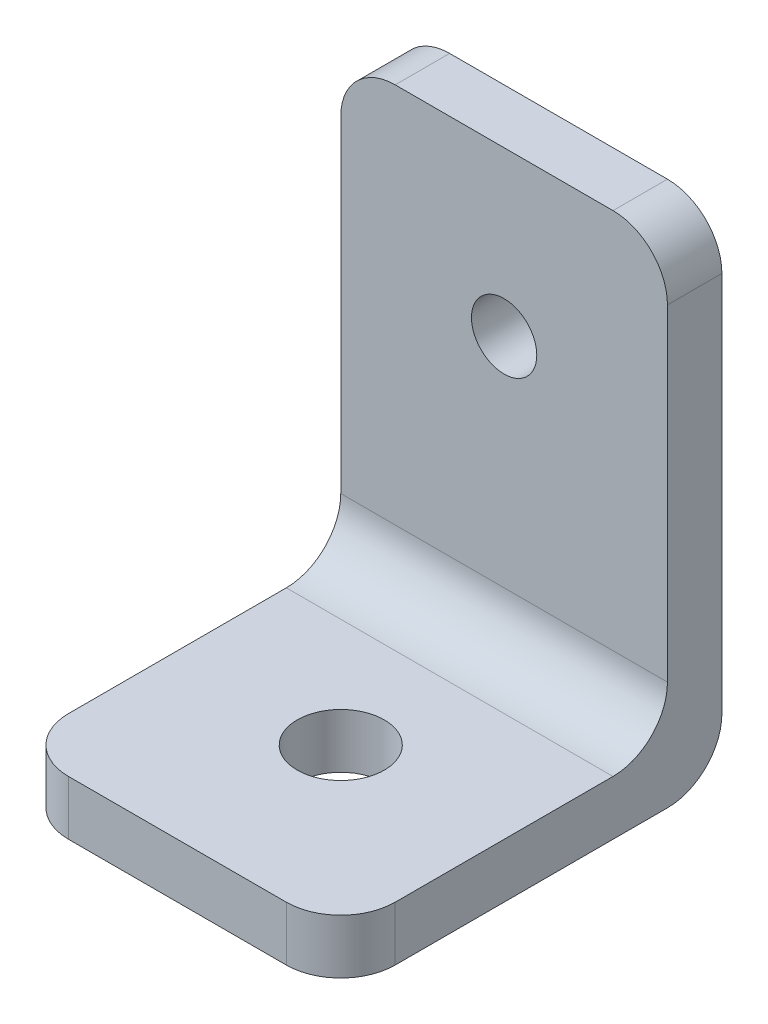
SolidWorks part; units mm, degrees
material "1023 Carbon Steel Sheet (SS)"
ref_plane "Front Plane" through (0, 0, 0) normal (0, 0, 1) x (1, 0, 0)
ref_plane "Top Plane" through (0, 0, 0) normal (0, 1, 0) x (1, 0, 0)
ref_plane "Right Plane" through (0, 0, 0) normal (1, 0, 0) x (0, 0, -1)
sketch "Sketch1" plane through (0, 0, 0) normal (0, 0, 1) x (1, 0, 0)
  line L0 (0, 0) -> (0, 45)
  line L1 (0, 45) -> (30, 45)
  line L2 (30, 45) -> (30, 0)
  line L3 (30, 0) -> (0, 0)
  line L4 (15, 45) -> (15, 30) construction
  circle A0 centre (15, 30) radius 3
extrude "Boss-Extrude1" add sketch "Sketch1" along normal blind 5
sketch "Sketch2" plane through (0, 0, 5) normal (0, 0, 1) x (1, 0, 0)
  line L0 (30, 0) -> (30, 45) construction
  line L1 (0, 0) -> (30, 0)
  line L2 (0, 0) -> (0, 5)
  line L3 (0, 5) -> (30, 5)
  line L4 (30, 0) -> (30, 5)
  line L5 (0, 0) -> (30, 5) construction
  line L6 (0, 5) -> (30, 0) construction
  point P4 (15, 2.5)
  dimension "D1" = 5
extrude "Boss-Extrude2" add sketch "Sketch2" along normal blind 30
sketch "Sketch3" plane through (0, 5, 0) normal (0, 1, 0) x (1, 0, 0)
  circle A0 centre (15, -20) radius 4
extrude "Cut-Extrude1" cut sketch "Sketch3" against normal blind 30
fillet "Fillet1" radius 5 6 edges at (15, 5, 5) (15, 0, 0) (0, 2.5, 35) (30, 2.5, 35) (0, 45, 2.5) (30, 45, 2.5)
